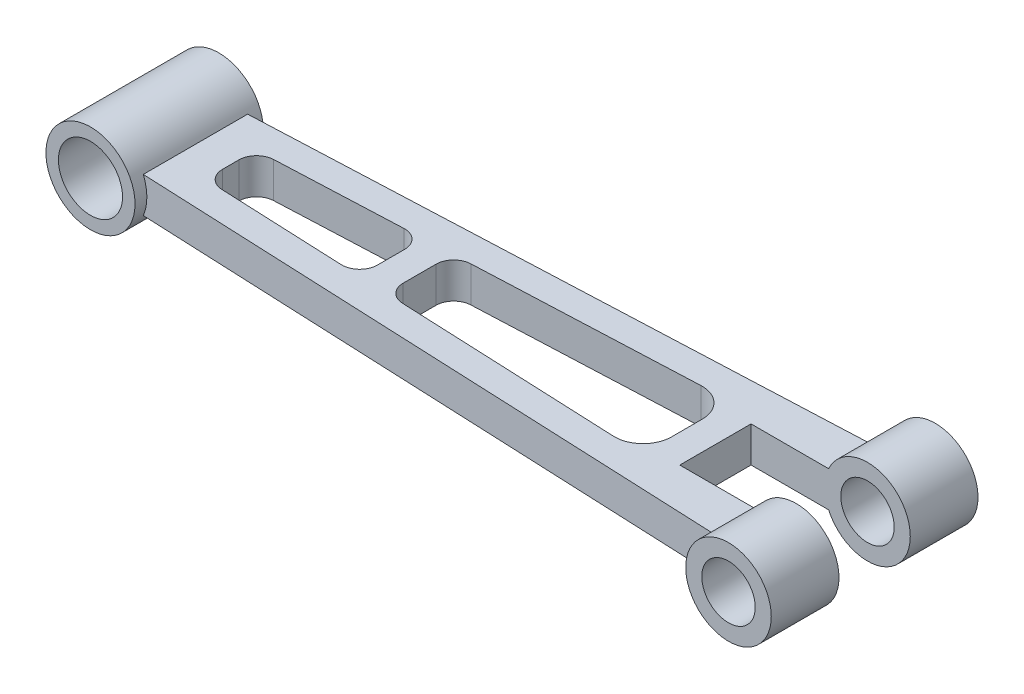
SolidWorks part; units mm, degrees
material "7075-T6 (SN)"
ref_plane "Front Plane" through (0, 0, 0) normal (0, 0, 1) x (1, 0, 0)
ref_plane "Top Plane" through (0, 0, 0) normal (0, 1, 0) x (1, 0, 0)
ref_plane "Right Plane" through (0, 0, 0) normal (1, 0, 0) x (0, 0, -1)
sketch "Sketch1" plane through (0, 0, 0) normal (0, 0, 1) x (1, 0, 0)
  line L0 (0, 0) -> (-95, 0) construction
  circle A0 centre (-95, 0) radius 12.5
  dimension "D2" = 25
  dimension "D1" = 95
extrude "Boss-Extrude1" add sketch "Sketch1" along normal mid plane 36
sketch "Sketch2" plane through (0, 0, 0) normal (0, 0, 1) x (1, 0, 0)
  line L0 (0, 0) -> (95, 0) construction
  circle A0 centre (95, 0) radius 12
  dimension "D2" = 24
  dimension "D1" = 95
extrude "Boss-Extrude2" add sketch "Sketch2" along normal mid plane 58 separate body
sketch "Sketch6" plane through (0, 0, 0) normal (0, 1, 0) x (1, 0, 0)
  line L0 (-95, 14.1394) -> (-95, 0) construction
  line L1 (-95, 0) -> (95, 0) construction
  line L3 (-95, 14.1394) -> (-95, -14.1394)
  line L4 (-95, 14.1394) -> (95, 22.435)
  line L5 (-95, -14.1394) -> (95, -22.435)
  line L7 (95, 22.435) -> (95, -22.435)
  point P11 (-55, 18.26)
  dimension "D1" = 5
extrude "Boss-Extrude4" add sketch "Sketch6" along normal mid plane 10 contours L7 L4 L3 L5
sketch "Sketch7" plane through (0, 5, 0) normal (0, 1, 0) x (1, 0, 0)
  line L0 (107.3306, 0) -> (62.3306, 0) construction
  line L2 (62.3306, 10) -> (124.9112, 10)
  line L3 (62.3306, 10) -> (62.3306, -10)
  line L4 (62.3306, -10) -> (124.9112, -10)
  line L5 (124.9112, 10) -> (124.9112, -10)
  dimension "D1" = 45
  dimension "D2" = 10
  dimension "D3" = 10
extrude "Cut-Extrude2" cut sketch "Sketch7" against normal mid plane 124
sketch "Sketch8" plane through (0, 5, 0) normal (0, 1, 0) x (1, 0, 0)
  line L0 (54.3306, 0) -> (-20.6694, 0) construction
  line L1 (62.3306, 10) -> (62.3306, -10) construction
  line L2 (-20.6694, 9.3771) -> (-20.6694, -9.3771) construction
  line L3 (-68.8875, -7.2719) -> (-33.8875, -8.8)
  line L4 (-83.1946, 6.6472) -> (84.4402, 13.9663)
  line L5 (-68.8875, 7.2719) -> (-33.8875, 8.8)
  line L6 (-20.6694, 4.5907) -> (-20.6694, -4.5907)
  line L7 (54.3306, 4.2948) -> (54.3306, -4.2948)
  line L8 (-28.6694, 3.8048) -> (-28.6694, -3.8048)
  line L9 (-28.6694, 0) -> (-73.6694, 0) construction
  line L10 (-73.6694, 2.2766) -> (-73.6694, -2.2766)
  line L11 (-15.8875, 9.5859) -> (45.9817, 12.2872)
  line L12 (-15.8875, -9.5859) -> (45.9817, -12.2872)
  line L13 (-28.6694, 9.3771) -> (-28.6694, -9.3771) construction
  arc A0 (-33.8875, 8.8) -> (-28.6694, 3.8048) centre (-33.6694, 3.8048) cw
  arc A1 (-33.8875, -8.8) -> (-28.6694, -3.8048) centre (-33.6694, -3.8048) ccw
  arc A2 (-73.6694, -2.2766) -> (-68.8875, -7.2719) centre (-68.6694, -2.2766) ccw
  arc A3 (-73.6694, 2.2766) -> (-68.8875, 7.2719) centre (-68.6694, 2.2766) cw
  arc A4 (-20.6694, -4.5907) -> (-15.8875, -9.5859) centre (-15.6694, -4.5907) ccw
  arc A5 (-20.6694, 4.5907) -> (-15.8875, 9.5859) centre (-15.6694, 4.5907) cw
  arc A6 (54.3306, -4.2948) -> (45.9817, -12.2872) centre (46.3306, -4.2948) cw
  arc A7 (54.3306, 4.2948) -> (45.9817, 12.2872) centre (46.3306, 4.2948) ccw
  point P12 (-20.6694, 0)
  point P15 (54.3306, 0)
  point P21 (-73.6694, 0)
  point P33 (-20.6694, -9.3771)
  dimension "D6" = 5
  dimension "D7" = 5
  dimension "D8" = 8
  dimension "D1" = 8
  dimension "D2" = 75
  dimension "D5" = 45
  dimension "D3" = 8
  dimension "D4" = 8
extrude "Cut-Extrude3" cut sketch "Sketch8" against normal mid plane 124
sketch "Sketch9" plane through (0, 0, 0) normal (0, 0, 1) x (1, 0, 0)
  circle A0 centre (-95, 0) radius 9
  circle A1 centre (95, 0) radius 7.5
  dimension "D1" = 18
  dimension "D2" = 15
extrude "Cut-Extrude4" cut sketch "Sketch9" against normal mid plane 124
